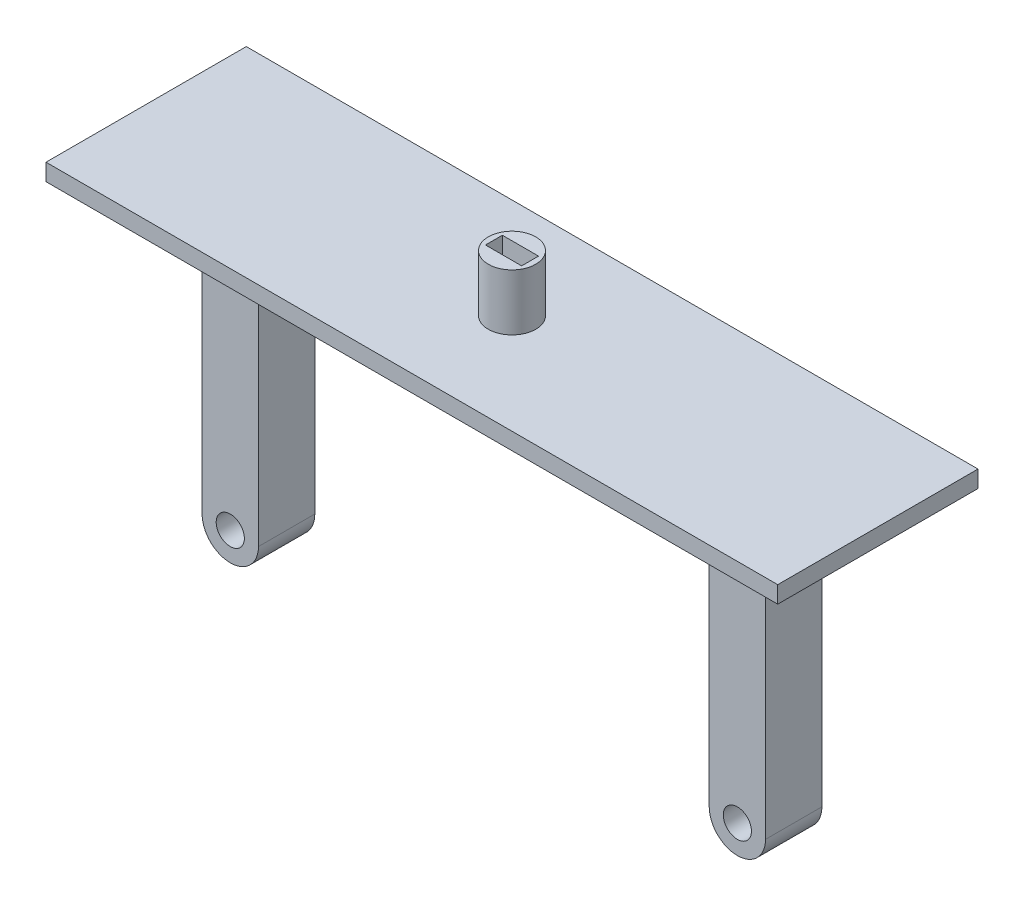
SolidWorks part; units mm, degrees
ref_plane "Front Plane" through (0, 0, 0) normal (0, 0, 1) x (1, 0, 0)
ref_plane "Top Plane" through (0, 0, 0) normal (0, 1, 0) x (1, 0, 0)
ref_plane "Right Plane" through (0, 0, 0) normal (1, 0, 0) x (0, 0, -1)
sketch "Sketch1" plane through (0, 0, 0) normal (0, 0, 1) x (1, 0, 0)
  line L1 (55, -1.5) -> (-55, -1.5)
  line L2 (55, -1.5) -> (55, 1.5)
  line L3 (55, 1.5) -> (-55, 1.5)
  line L4 (-55, -1.5) -> (-55, 1.5)
  line L5 (55, -1.5) -> (-55, 1.5) construction
  line L6 (55, 1.5) -> (-55, -1.5) construction
  line L7 (-50, -1.5) -> (-40, -1.5)
  line L8 (-50, -1.5) -> (-50, -51.5)
  line L9 (-50, -51.5) -> (-40, -51.5)
  line L10 (-40, -1.5) -> (-40, -51.5)
  line L11 (50, -1.5) -> (40, -1.5)
  line L12 (50, -1.5) -> (50, -51.5)
  line L13 (50, -51.5) -> (40, -51.5)
  line L14 (40, -1.5) -> (40, -51.5)
  arc A0 (-40, -51.5) -> (-50, -51.5) centre (-45, -51.5) cw
  circle A1 centre (-45, -51.5) radius 2.5
  arc A2 (40, -51.5) -> (50, -51.5) centre (45, -51.5) ccw
  circle A3 centre (45, -51.5) radius 2.5
  point P0 (0, 0)
  dimension "D6" = 50
  dimension "D1" = 110
  dimension "D2" = 3
  dimension "D3" = 50
  dimension "D4" = 40
  dimension "D5" = 10
  dimension "D7" = 10
  dimension "D8" = 40
extrude "Boss-Extrude1" add sketch "Sketch1" along normal mid plane 10 contours A1 L9 A0 | A1 L9 L10 L1 L8 | L4 L1 L2 L3 | A3 L13 L12 L1 L14 | A3 L13 A2
sketch "Sketch2" plane through (0, 1.5, 0) normal (0, 1, 0) x (1, 0, 0)
  line L1 (64.9334, -17.7728) -> (-64.9334, -17.7728)
  line L2 (64.9334, -17.7728) -> (64.9334, 17.7728)
  line L3 (64.9334, 17.7728) -> (-64.9334, 17.7728)
  line L4 (-64.9334, -17.7728) -> (-64.9334, 17.7728)
  line L5 (64.9334, -17.7728) -> (-64.9334, 17.7728) construction
  line L6 (64.9334, 17.7728) -> (-64.9334, -17.7728) construction
  point P0 (0, 0)
extrude "Boss-Extrude2" add sketch "Sketch2" against normal blind 3
sketch "Sketch3" plane through (0, 1.5, 0) normal (0, 1, 0) x (1, 0, 0)
  line L1 (3.21, -1.5) -> (-3.21, -1.5)
  line L2 (3.21, -1.5) -> (3.21, 1.5)
  line L3 (3.21, 1.5) -> (-3.21, 1.5)
  line L4 (-3.21, -1.5) -> (-3.21, 1.5)
  line L5 (3.21, -1.5) -> (-3.21, 1.5) construction
  line L6 (3.21, 1.5) -> (-3.21, -1.5) construction
  point P1 (0, 0)
  dimension "D1" = 6.42
  dimension "D2" = 3
extrude "Cut-Extrude1" cut sketch "Sketch3" against normal through all
sketch "Sketch4" plane through (0, 1.5, 0) normal (0, 1, 0) x (1, 0, 0)
  line L1 (3.21, -1.5) -> (-3.21, -1.5)
  line L2 (3.21, -1.5) -> (3.21, 1.5)
  line L3 (3.21, 1.5) -> (-3.21, 1.5)
  line L4 (-3.21, -1.5) -> (-3.21, 1.5)
  line L5 (3.21, -1.5) -> (-3.21, 1.5) construction
  line L6 (3.21, 1.5) -> (-3.21, -1.5) construction
  circle A0 centre (0, 0) radius 4.2091
  dimension "D1" = 8.4183
extrude "Boss-Extrude3" add sketch "Sketch4" along normal blind 10
